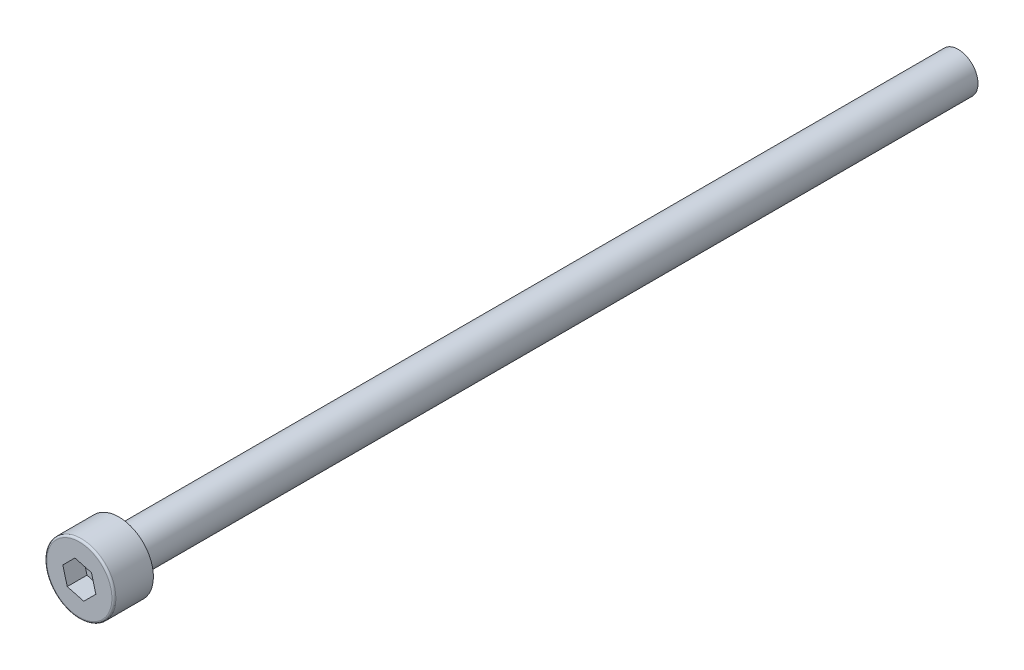
SolidWorks part; units mm, degrees
ref_plane "前视基准面" through (0, 0, 0) normal (0, 0, 1) x (1, 0, 0)
ref_plane "上视基准面" through (0, 0, 0) normal (0, 1, 0) x (1, 0, 0)
ref_plane "右视基准面" through (0, 0, 0) normal (1, 0, 0) x (0, 0, -1)
sketch "草图1" plane through (0, 0, 0) normal (0, 0, 1) x (1, 0, 0)
  circle A0 centre (0, 0) radius 3.5
  dimension "D1" = 7
extrude "凸台-拉伸1" add sketch "草图1" along normal blind 4
sketch "草图2" plane through (0, 0, 4) normal (0, 0, 1) x (1, 0, 0)
  line L1 (-1.2247, -1.2247) -> (0.4483, -1.673)
  line L2 (0.4483, -1.673) -> (1.673, -0.4483)
  line L3 (1.673, -0.4483) -> (1.2247, 1.2247)
  line L4 (1.2247, 1.2247) -> (-0.4483, 1.673)
  line L5 (-0.4483, 1.673) -> (-1.673, 0.4483)
  line L6 (-1.673, 0.4483) -> (-1.2247, -1.2247)
  circle A0 centre (0, 0) radius 1.5 construction
  dimension "D1" = 3
extrude "切除-拉伸1" cut sketch "草图2" against normal blind 2
sketch "草图3" plane through (0, 0, 0) normal (0, 0, -1) x (-1, 0, 0)
  circle A0 centre (0, 0) radius 2
  dimension "D1" = 4
extrude "凸台-拉伸2" add sketch "草图3" along normal blind 85
fillet "圆角1" radius 0.2 1 edges at (3.5, 0, 4)
